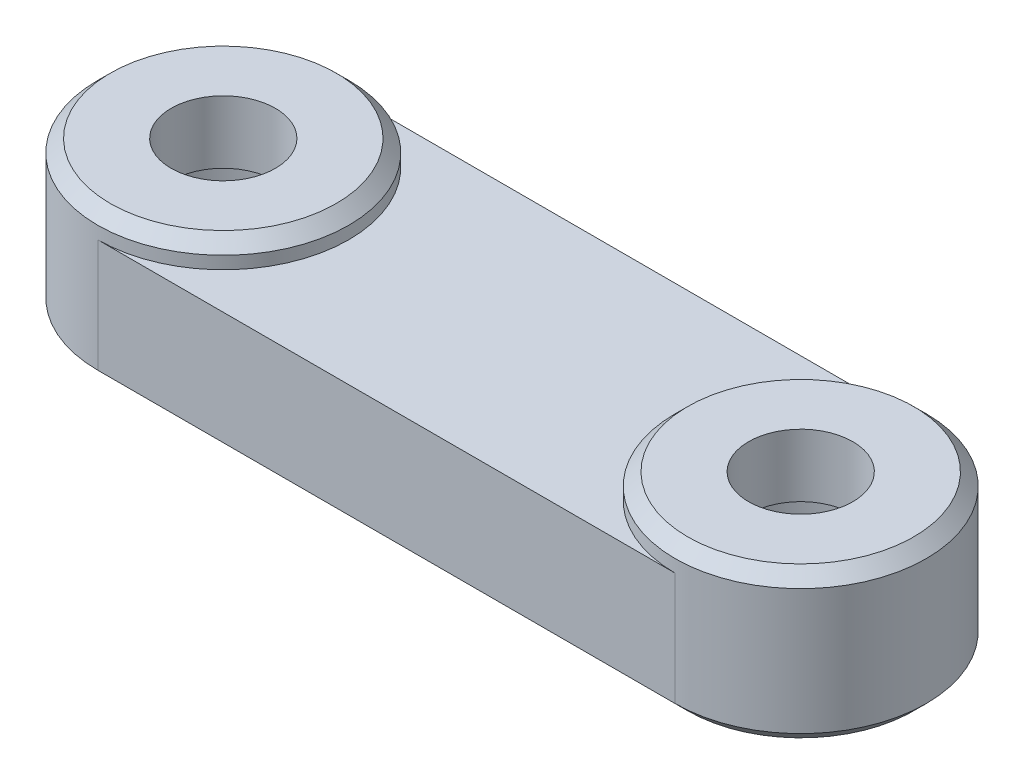
SolidWorks part; units mm, degrees
material "POM 乙缩醛共聚物"
ref_plane "前视基准面" through (0, 0, 0) normal (0, 0, 1) x (1, 0, 0)
ref_plane "上视基准面" through (0, 0, 0) normal (0, 1, 0) x (1, 0, 0)
ref_plane "右视基准面" through (0, 0, 0) normal (1, 0, 0) x (0, 0, -1)
sketch "草图1" plane through (0, 0, 0) normal (0, 1, 0) x (1, 0, 0)
  line L0 (0, 0) -> (23, 0) construction
  line L1 (0, 5) -> (23, 5)
  line L4 (0, -5) -> (23, -5)
  arc A2 (0, 5) -> (0, -5) centre (0, 0) ccw
  arc A3 (23, -5) -> (23, 5) centre (23, 0) ccw
  point P3 (11.5, 0)
  dimension "D1" = 10
  dimension "D2" = 23
extrude "凸台-拉伸1" add sketch "草图1" along normal blind 6
sketch "草图2" plane through (0, 0, 0) normal (0, 0, 1) x (1, 0, 0)
  line L0 (0, 6) -> (0, 0) construction
  line L1 (0, 0) -> (-3.75, 0)
  line L2 (-5, 0) -> (0, 0) construction
  line L3 (-3.75, 0) -> (-3.75, 3.5)
  line L4 (-3.75, 3.5) -> (-2.075, 3.5)
  line L5 (-2.075, 3.5) -> (-2.075, 6)
  line L6 (0, 6) -> (-5, 6) construction
  line L7 (-2.075, 6) -> (0, 6)
  line L8 (0, 6) -> (0, 0)
  dimension "D1" = 4.15
  dimension "D2" = 7.5
  dimension "D3" = 3.5
revolve "切除-旋转1" cut sketch "草图2" angle 360 about L0
sketch "草图3" plane through (0, 0, 0) normal (0, 0, 1) x (1, 0, 0)
  line L0 (23, 0) -> (23, 6) construction
  line L1 (23, 0) -> (19.25, 0)
  line L2 (0, 0) -> (23, 0) construction
  line L3 (19.25, 0) -> (19.25, 3.5)
  line L4 (19.25, 3.5) -> (20.925, 3.5)
  line L5 (20.925, 3.5) -> (20.925, 6)
  line L6 (0, 6) -> (23, 6) construction
  line L7 (20.925, 6) -> (23, 6)
  line L8 (23, 0) -> (23, 6)
  dimension "D1" = 4.15
  dimension "D2" = 7.5
  dimension "D3" = 3.5
revolve "切除-旋转2" cut sketch "草图3" angle 360 about L0
sketch "草图4" plane through (0, 6, 0) normal (0, 1, 0) x (1, 0, 0)
  line L1 (-6.7787, 9.2955) -> (30.587, 9.2955)
  line L2 (-6.7787, 9.2955) -> (-6.7787, -8.8914)
  line L3 (-6.7787, -8.8914) -> (30.587, -8.8914)
  line L4 (30.587, 9.2955) -> (30.587, -8.8914)
  circle A0 centre (0, 0) radius 5
  circle A1 centre (23, 0) radius 5
  arc A2 (0, 5) -> (0, -5) centre (0, 0) ccw construction
  arc A3 (23, -5) -> (23, 5) centre (23, 0) ccw construction
extrude "切除-拉伸1" cut sketch "草图4" against normal blind 1
chamfer "倒角1" distance 0.5 angle 45 6 edges at (23, 6, 5) (0, 6, 5) (11.5, 0, -5) (-5, 0, 0) (28, 0, 0) (11.5, 0, 5)
